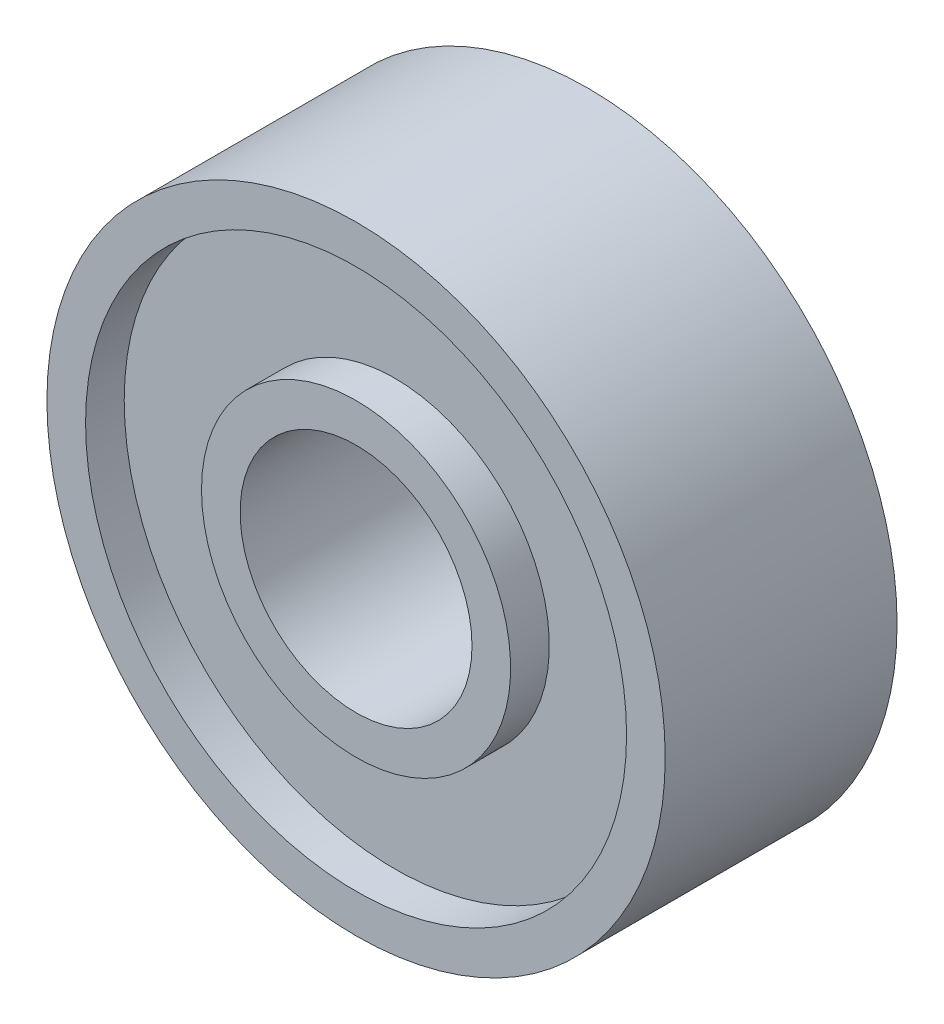
SolidWorks part; units mm, degrees
ref_plane "Front Plane" through (0, 0, 0) normal (0, 0, 1) x (1, 0, 0)
ref_plane "Top Plane" through (0, 0, 0) normal (0, 1, 0) x (1, 0, 0)
ref_plane "Right Plane" through (0, 0, 0) normal (1, 0, 0) x (0, 0, -1)
sketch "Sketch1" plane through (0, 0, 0) normal (0, 0, 1) x (1, 0, 0)
  circle A0 centre (0, 0) radius 1.5
  circle A1 centre (0, 0) radius 4
  dimension "D1" = 3
  dimension "D2" = 8
extrude "Boss-Extrude1" add sketch "Sketch1" along normal mid plane 3
sketch "Sketch2" plane through (0, 0, 1.5) normal (0, 0, 1) x (1, 0, 0)
  circle A2 centre (0, 0) radius 2
  circle A3 centre (0, 0) radius 2
  circle A5 centre (0, 0) radius 3.5
  circle A6 centre (0, 0) radius 3.5
  dimension "D1" = 0.5
  dimension "D2" = 0.5
extrude "Cut-Extrude1" cut sketch "Sketch2" against normal blind 0.5 and the other way through all
mirror "Mirror1" about plane through (0, 0, 0) normal (0, 0, 1) of "Cut-Extrude1"
